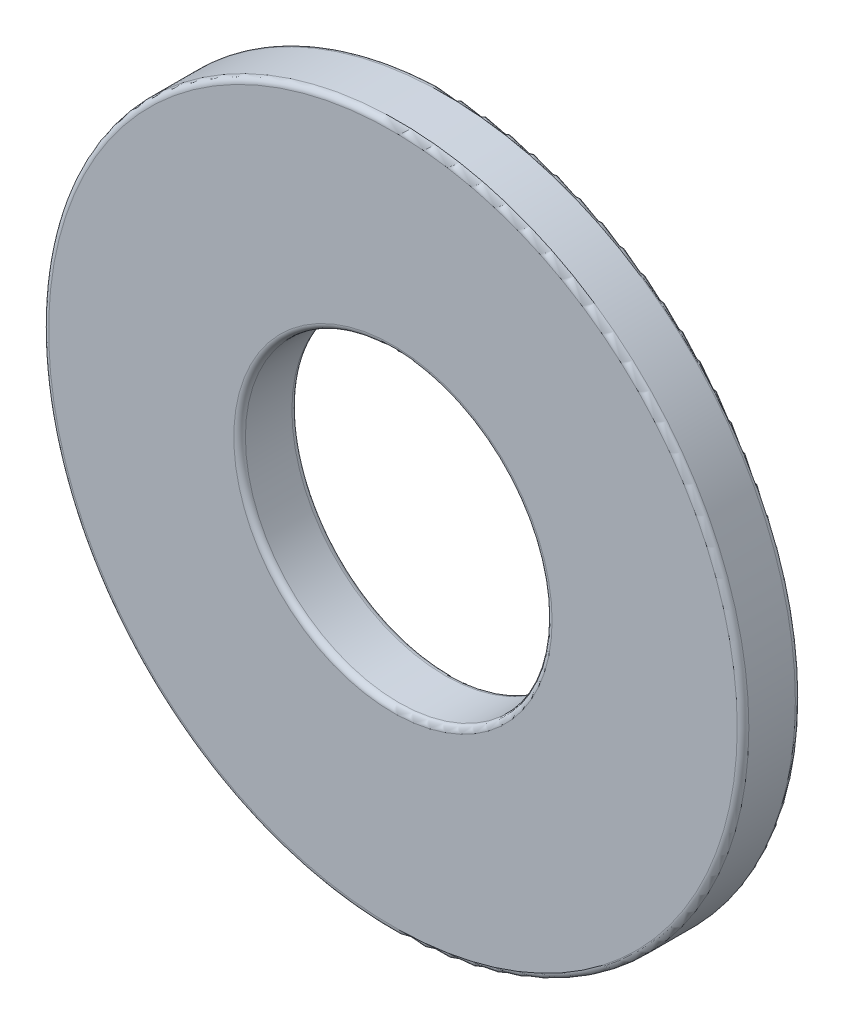
SolidWorks part; units mm, degrees
ref_plane "Front Plane" through (0, 0, 0) normal (0, 0, 1) x (1, 0, 0)
ref_plane "Top Plane" through (0, 0, 0) normal (0, 1, 0) x (1, 0, 0)
ref_plane "Right Plane" through (0, 0, 0) normal (1, 0, 0) x (0, 0, -1)
sketch "Sketch1" plane through (0, 0, 0) normal (0, 0, 1) x (1, 0, 0)
  circle A0 centre (0, 0) radius 12.7 construction
  circle A1 centre (0, 0) radius 5.5626 construction
  dimension "OD" = 25.4
  dimension "ID" = 11.1252
sketch "Sketch2" plane through (0, 0, 0) normal (1, 0, 0) x (0, 0, -1)
  line L0 (-1.0541, -12.7) -> (1.0541, -12.7) construction
  point P0 (0.8001, -12.7)
  point P4 (0, -12.7)
  dimension "Thickness Max" = 2.1082
  dimension "Thickness Min" = 1.8542
sketch "Sketch3" plane through (0, 0, 0) normal (0, 0, 1) x (1, 0, 0)
  circle A0 centre (0, 0) radius 12.7 construction
  circle A1 centre (0, 0) radius 12.7
  circle A2 centre (0, 0) radius 5.5626 construction
  circle A3 centre (0, 0) radius 5.5626
extrude "Boss-Extrude1" add sketch "Sketch3" against normal up to vertex (1.0541 mm away) and the other way up to vertex (1.0541 mm away) up to point (0, -12.7, -1.0541) other way up to point (0, -12.7, 1.0541)
fillet "Fillet1" radius 0.2108 4 edges at (12.7, 0, -1.0541) (5.5626, 0, -1.0541) (5.5626, 0, 1.0541) (12.7, 0, 1.0541)
equation "\"D1@Fillet1\" = \"Thickness Max@Sketch2\" * 0.1"
